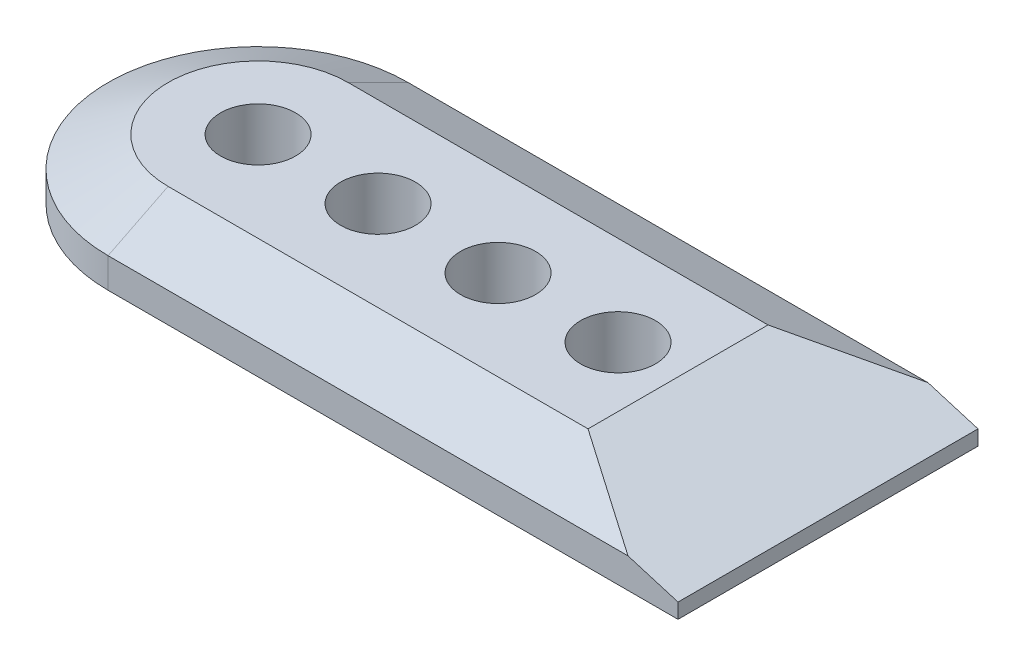
SolidWorks part; units mm, degrees
ref_plane "Front Plane" through (0, 0, 0) normal (0, 0, 1) x (1, 0, 0)
ref_plane "Top Plane" through (0, 0, 0) normal (0, 1, 0) x (1, 0, 0)
ref_plane "Right Plane" through (0, 0, 0) normal (1, 0, 0) x (0, 0, -1)
sketch "Sketch1" plane through (0, 0, 0) normal (0, 1, 0) x (1, 0, 0)
  line L0 (-120.65, 0) -> (0, 0)
  line L1 (0, 0) -> (0, 63.5)
  line L2 (0, 63.5) -> (-120.65, 63.5)
  arc A0 (-120.65, 63.5) -> (-120.65, 0) centre (-120.65, 31.75) ccw
  point P6 (0, 0)
  point P7 (0, 0)
  point P8 (-152.4, 31.75)
  point P9 (0, 0)
  dimension "D1" = 31.75
  dimension "D2" = 152.4
extrude "Boss-Extrude1" add sketch "Sketch1" along normal blind 12.7
chamfer "Chamfer1" distance 9.525 distance2 31.75 1 edges at (0, 12.7, -31.75)
chamfer "Chamfer2" distance 6.35 distance2 12.7 3 edges at (-76.2, 12.7, -63.5) (-152.4, 12.7, -31.75) (-76.2, 12.7, 0)
sketch "Sketch3" plane through (0, 12.7, 0) normal (0, 1, 0) x (1, 0, 0)
  circle A0 centre (-120.65, 31.75) radius 7.9375
  circle A1 centre (-95.25, 31.75) radius 7.9375
  circle A2 centre (-69.85, 31.75) radius 7.9375
  circle A3 centre (-44.45, 31.75) radius 7.9375
  point P3 (-44.3085, 31.75)
  point P4 (-79.394, 31.75)
  dimension "D1" = 15.875
  dimension "D3" = 25.4
  dimension "D2" = 4
extrude "Cut-Extrude1" cut sketch "Sketch3" against normal through all
